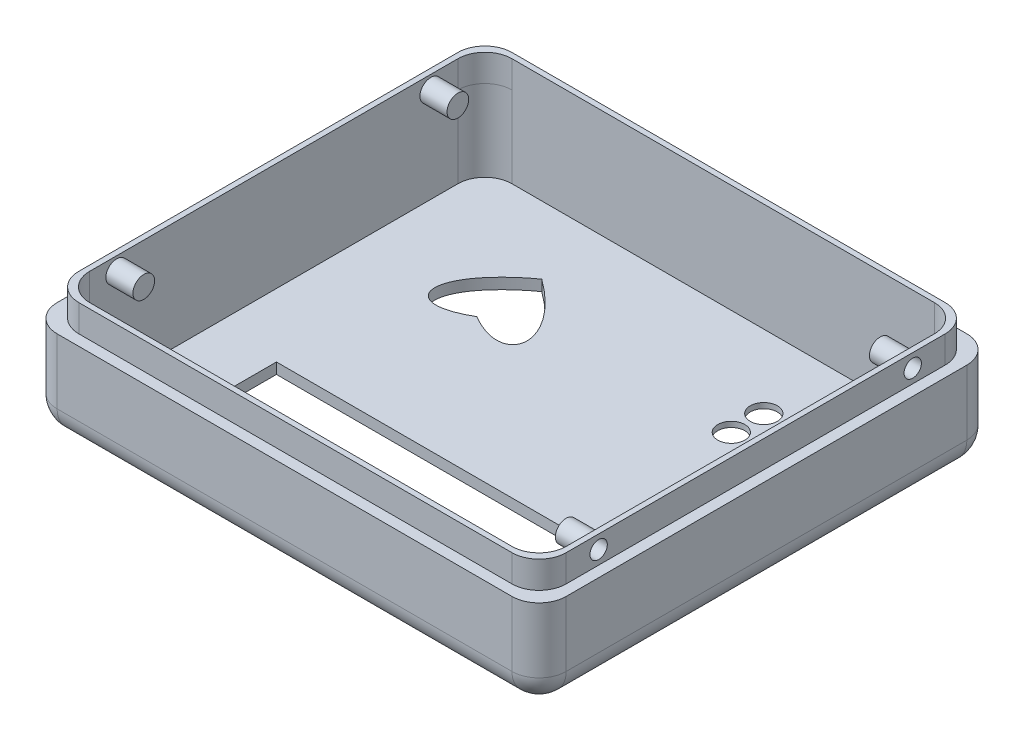
SolidWorks part; units mm, degrees
ref_plane "Front Plane" through (0, 0, 0) normal (0, 0, 1) x (1, 0, 0)
ref_plane "Top Plane" through (0, 0, 0) normal (0, 1, 0) x (1, 0, 0)
ref_plane "Right Plane" through (0, 0, 0) normal (1, 0, 0) x (0, 0, -1)
sketch "Sketch1" plane through (0, 0, 0) normal (0, 1, 0) x (1, 0, 0)
  line L1 (-47, 42) -> (47, 42)
  line L2 (-47, 42) -> (-47, -42)
  line L3 (-47, -42) -> (47, -42)
  line L4 (47, 42) -> (47, -42)
  line L5 (-47, 42) -> (47, -42) construction
  line L6 (-47, -42) -> (47, 42) construction
  point P0 (0, 0)
  dimension "D1" = 84
  dimension "D2" = 94
extrude "Boss-Extrude1" add sketch "Sketch1" along normal blind 17
sketch "Sketch2" plane through (0, 17, 0) normal (0, 1, 0) x (1, 0, 0)
  line L1 (-44, 39) -> (44, 39)
  line L2 (-44, 39) -> (-44, -39)
  line L3 (-44, -39) -> (44, -39)
  line L4 (44, 39) -> (44, -39)
  line L5 (-44, 39) -> (44, -39) construction
  line L6 (-44, -39) -> (44, 39) construction
  point P0 (0, 0)
  dimension "D1" = 78
  dimension "D2" = 88
extrude "Cut-Extrude1" cut sketch "Sketch2" against normal blind 15
fillet "Fillet1" radius 5 12 edges at (44, 9.5, -39) (44, 9.5, 39) (-44, 9.5, 39) (-44, 9.5, -39) (0, 0, -42) (47, 8.5, -42) (47, 0, 0) (0, 0, 42) (-47, 0, 0) (47, 8.5, 42) (-47, 8.5, 42) (-47, 8.5, -42)
sketch "Sketch4" plane through (0, 17, 0) normal (0, 1, 0) x (1, 0, 0)
  line L1 (-45, 40) -> (45, 40)
  line L2 (-45, 40) -> (-45, -40)
  line L3 (-45, -40) -> (45, -40)
  line L4 (45, 40) -> (45, -40)
  line L5 (-45, 40) -> (45, -40) construction
  line L6 (-45, -40) -> (45, 40) construction
  point P0 (0, 0)
  dimension "D1" = 80
  dimension "D2" = 90
extrude "Boss-Extrude3" add sketch "Sketch4" along normal blind 5
sketch "Sketch5" plane through (0, 22, 0) normal (0, 1, 0) x (1, 0, 0)
  line L1 (-44, 39) -> (44, 39)
  line L2 (-44, 39) -> (-44, -39)
  line L3 (-44, -39) -> (44, -39)
  line L4 (44, 39) -> (44, -39)
  line L5 (-44, 39) -> (44, -39) construction
  line L6 (-44, -39) -> (44, 39) construction
  point P0 (0, 0)
  dimension "D1" = 88
  dimension "D2" = 78
extrude "Cut-Extrude2" cut sketch "Sketch5" against normal blind 5
fillet "Fillet2" radius 5 8 edges at (44, 19.5, 39) (-44, 19.5, -39) (-44, 19.5, 39) (44, 19.5, -39) (45, 19.5, -40) (-45, 19.5, -40) (-45, 19.5, 40) (45, 19.5, 40)
sketch "Sketch6" plane through (-44, 0, 0) normal (1, 0, 0) x (0, 0, -1)
  line L0 (34, 17) -> (34, 22) construction
  line L1 (34, 22) -> (-34, 22) construction
  line L2 (-34, 22) -> (-34, 17) construction
  circle A0 centre (29, 19.5) radius 2
  circle A1 centre (-29, 19.5) radius 2
  dimension "D1" = 4
  dimension "D2" = 4
  dimension "D3" = 5
  dimension "D4" = 2.5
  dimension "D5" = 5
  dimension "D6" = 2.5
extrude "Boss-Extrude4" add sketch "Sketch6" along normal blind 5
sketch "Sketch7" plane through (44, 0, 0) normal (-1, 0, 0) x (0, 0, 1)
  line L0 (34, 22) -> (-34, 22) construction
  line L1 (34, 17) -> (34, 22) construction
  line L2 (-34, 22) -> (-34, 17) construction
  circle A0 centre (29, 19.5) radius 2
  circle A1 centre (-29, 19.5) radius 2
  dimension "D1" = 4
  dimension "D2" = 4
  dimension "D3" = 2.5
  dimension "D4" = 5
  dimension "D5" = 5
  dimension "D6" = 2.5
extrude "Boss-Extrude5" add sketch "Sketch7" along normal blind 5
sketch "Sketch8" plane through (45, 0, 0) normal (1, 0, 0) x (0, 0, -1)
  line L0 (-35, 22) -> (35, 22) construction
  line L3 (-35, 22) -> (-35, 17) construction
  line L8 (35, 17) -> (35, 22) construction
  circle A0 centre (29, 19.5) radius 1.6
  circle A1 centre (-29, 19.5) radius 1.6
  point P15 (35, 19.5)
  dimension "D1" = 3.2
  dimension "D2" = 3.2
  dimension "D3" = 2.5
  dimension "D4" = 2.5
  dimension "D5" = 6
  dimension "D6" = 6
extrude "Cut-Extrude3" cut sketch "Sketch8" against normal blind 4
sketch "Sketch9" plane through (-45, 0, 0) normal (-1, 0, 0) x (0, 0, 1)
  line L0 (-35, 22) -> (-35, 17) construction
  line L1 (35, 17) -> (35, 22) construction
  line L2 (-35, 22) -> (35, 22) construction
  circle A0 centre (-29, 19.5) radius 1.6
  circle A1 centre (29, 19.5) radius 1.6
  dimension "D1" = 3.2
  dimension "D2" = 3.2
  dimension "D3" = 6
  dimension "D4" = 6
  dimension "D5" = 2.5
  dimension "D6" = 2.5
extrude "Cut-Extrude4" cut sketch "Sketch9" against normal blind 4
sketch "Sketch10" plane through (0, 0, 0) normal (0, -1, 0) x (1, 0, 0)
  line L0 (42, -37) -> (42, 37) construction
  line L1 (-32.25, 25.75) -> (32.25, 25.75)
  line L2 (-32.25, 25.75) -> (-32.25, 11.25)
  line L3 (-32.25, 11.25) -> (32.25, 11.25)
  line L4 (32.25, 25.75) -> (32.25, 11.25)
  line L5 (-32.25, 25.75) -> (32.25, 11.25) construction
  line L6 (-32.25, 11.25) -> (32.25, 25.75) construction
  point P0 (0, 18.5)
  dimension "D1" = 14.5
  dimension "D2" = 64.5
  dimension "D3" = 18.5
  dimension "D4" = 42
extrude "Cut-Extrude5" cut sketch "Sketch10" against normal blind 2
sketch "Sketch11" plane through (0, 0, 0) normal (0, -1, 0) x (1, 0, 0)
  line L0 (42, -37) -> (42, 37) construction
  line L1 (16.5, -12.5) -> (25.5, -12.5)
  line L2 (16.5, -12.5) -> (16.5, -32.5)
  line L3 (16.5, -32.5) -> (25.5, -32.5)
  line L4 (25.5, -12.5) -> (25.5, -32.5)
  line L5 (16.5, -12.5) -> (25.5, -32.5) construction
  line L6 (16.5, -32.5) -> (25.5, -12.5) construction
  point P0 (21, -22.5)
  dimension "D1" = 20
  dimension "D2" = 9
  dimension "D3" = 16.5
  dimension "D4" = 12.5
extrude "Cut-Extrude6" cut sketch "Sketch11" against normal blind 1
fillet "Fillet3" radius 1 4 edges at (25.5, 0.5, -32.5) (16.5, 0.5, -32.5) (25.5, 0.5, -12.5) (16.5, 0.5, -12.5)
sketch "Sketch12" plane through (0, 1, 0) normal (0, -1, 0) x (1, 0, 0)
  line L0 (17.5, -32.5) -> (24.5, -32.5) construction
  line L1 (25.5, -31.5) -> (25.5, -13.5) construction
  circle A0 centre (21, -19.5) radius 2.5
  circle A1 centre (21, -25.5) radius 2.5
  dimension "D1" = 5
  dimension "D2" = 5
  dimension "D3" = 7
  dimension "D4" = 4.5
  dimension "D5" = 6
  dimension "D6" = 4.5
extrude "Cut-Extrude7" cut sketch "Sketch12" against normal blind 1
sketch "Sketch14" plane through (0, 0, 0) normal (0, -1, 0) x (1, 0, 0)
  line L1 (-21, -14.5) -> (-31.1384, -8.574) construction
  line L2 (-31.1384, -8.574) -> (-33.5098, -17.3736) construction
  line L3 (-33.5098, -17.3736) -> (-21, -26.5) construction
  line L4 (-42, 37) -> (-42, -37) construction
  line L5 (-42, -37) -> (42, -37) construction
  line L6 (-21, 8.6716) -> (-21, -46.04) construction
  line L7 (-21, -14.5) -> (-10.8616, -8.574) construction
  line L8 (-10.8616, -8.574) -> (-8.4902, -17.3736) construction
  line L9 (-8.4902, -17.3736) -> (-21, -26.5) construction
  spline S0 degree 3 poles (-21, -14.5) (-31.1384, -8.574) (-33.5098, -17.3736) (-21, -26.5) knots 0 0 0 0 1 1 1 1
  spline S1 degree 3 poles (-21, -14.5) (-10.8616, -8.574) (-8.4902, -17.3736) (-21, -26.5) knots 0 0 0 0 1 1 1 1
  dimension "D1" = 25
  dimension "D6" = 21
  dimension "D2" = 12
  dimension "D3" = 9.1135
  dimension "D4" = 11.7432
  dimension "D5" = 12.5098
  dimension "D7" = 22.5
extrude "Cut-Extrude8" cut sketch "Sketch14" against normal blind 2
